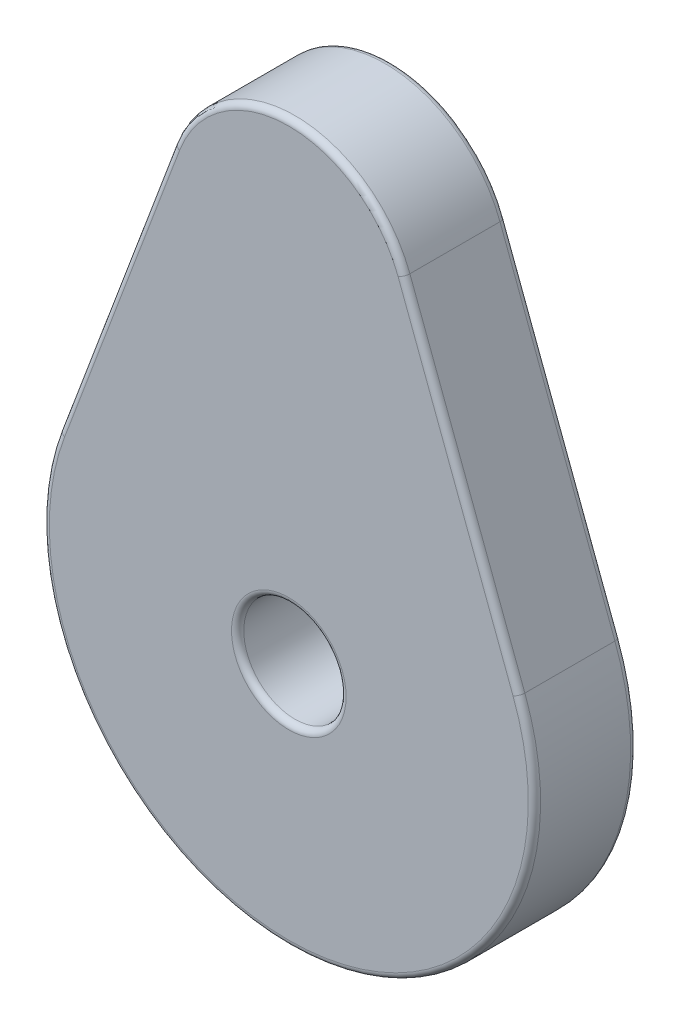
SolidWorks part; units mm, degrees
ref_plane "Front Plane" through (0, 0, 0) normal (0, 0, 1) x (1, 0, 0)
ref_plane "Top Plane" through (0, 0, 0) normal (0, 1, 0) x (1, 0, 0)
ref_plane "Right Plane" through (0, 0, 0) normal (1, 0, 0) x (0, 0, -1)
sketch "Sketch1" plane through (0, 0, 0) normal (0, 0, 1) x (1, 0, 0)
  line L0 (0, 69.2111) -> (0, -45.0988) construction
  line L1 (-88.0671, 0) -> (56.5154, 0) construction
  line L2 (-56.1597, 21.1207) -> (-28.0799, 95.7849)
  line L3 (56.1597, 21.1207) -> (28.0799, 95.7849)
  arc A0 (-56.1597, 21.1207) -> (56.1597, 21.1207) centre (0, 0) ccw
  arc A1 (28.0799, 95.7849) -> (-28.0799, 95.7849) centre (0, 85.2245) ccw
  circle A2 centre (0, 0) radius 12.5
  dimension "D1" = 120
  dimension "D2" = 60
  dimension "D4" = 25
  dimension "D3" = 85.2245
extrude "Boss-Extrude1" add sketch "Sketch1" along normal mid plane 25
fillet "Fillet1" radius 1.5 8 edges at (-42.1198, 58.4528, -12.5) (0, 115.2245, -12.5) (42.1198, 58.4528, -12.5) (-42.1198, 58.4528, 12.5) (0, 115.2245, 12.5) (42.1198, 58.4528, 12.5) (0, -60, -12.5) (0, -60, 12.5)
fillet "Fillet2" radius 1.5 2 edges at (12.5, 0, 12.5) (12.5, 0, -12.5)
